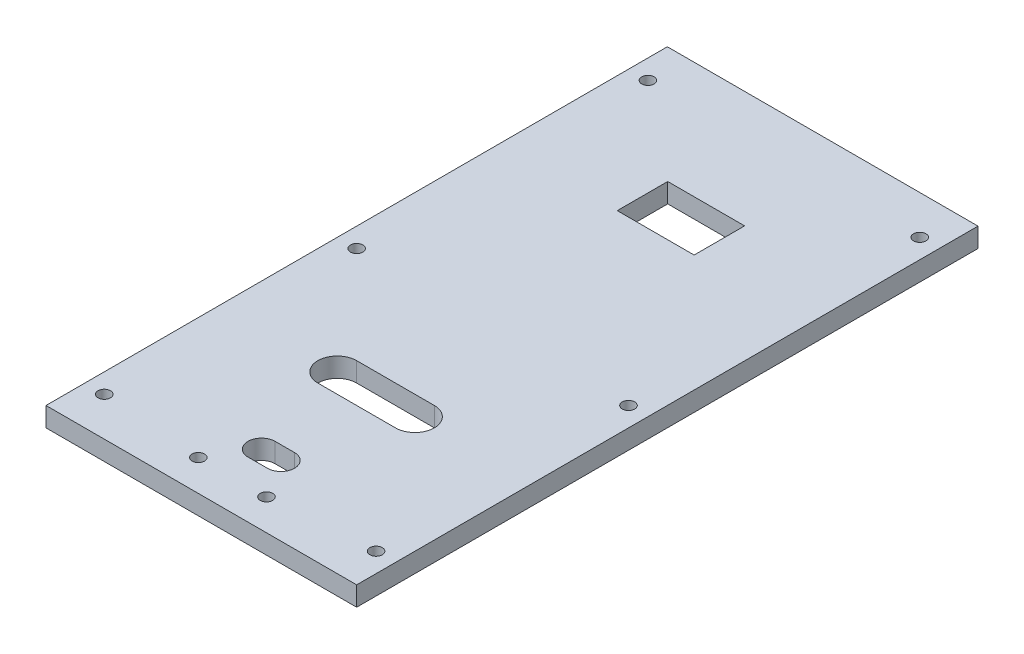
SolidWorks part; units mm, degrees
ref_plane "Plan de face" through (0, 0, 0) normal (0, 0, 1) x (1, 0, 0)
ref_plane "Plan de dessus" through (0, 0, 0) normal (0, 1, 0) x (1, 0, 0)
ref_plane "Plan de droite" through (0, 0, 0) normal (1, 0, 0) x (0, 0, -1)
sketch "Esquisse1" plane through (0, 0, 0) normal (0, 1, 0) x (1, 0, 0)
  line L1 (0, 0) -> (80, 0)
  line L2 (0, 0) -> (0, 160)
  line L3 (0, 160) -> (80, 160)
  line L4 (80, 0) -> (80, 160)
  dimension "D1" = 160
  dimension "D2" = 80
extrude "Boss.-Extru.1" add sketch "Esquisse1" along normal blind 5
sketch "Esquisse2" plane through (0, 0, 0) normal (0, 1, 0) x (1, 0, 0)
  line L0 (5, 160) -> (5, 0) construction
  line L1 (80, 160) -> (0, 160) construction
  line L2 (0, 0) -> (80, 0) construction
  line L3 (0, 160) -> (0, 0) construction
  line L4 (40, 160) -> (40, 0) construction
  circle A0 centre (5, 150) radius 1.6
  circle A1 centre (5, 75) radius 1.6
  circle A2 centre (5, 10) radius 1.6
  circle A3 centre (75, 10) radius 1.6
  circle A4 centre (75, 75) radius 1.6
  circle A5 centre (75, 150) radius 1.6
  dimension "D1" = 3.2
  dimension "D2" = 5
  dimension "D3" = 10
  dimension "D4" = 10
  dimension "D5" = 75
extrude "Enlèv. mat.-Extru.8" cut sketch "Esquisse2" along normal blind 10
sketch "Esquisse3" plane through (0, 0, 0) normal (0, 1, 0) x (1, 0, 0)
  line L0 (40, 160) -> (40, 0) construction
  line L1 (30.1, 130) -> (49.9, 130)
  line L2 (30.1, 130) -> (30.1, 117)
  line L3 (30.1, 117) -> (49.9, 117)
  line L4 (49.9, 130) -> (49.9, 117)
  line L5 (80, 160) -> (0, 160) construction
  line L6 (0, 0) -> (80, 0) construction
  point P10 (40, 130)
  dimension "D1" = 19.8
  dimension "D2" = 13
  dimension "D3" = 30
extrude "Enlèv. mat.-Extru.9" cut sketch "Esquisse3" along normal blind 10
sketch "Esquisse4" plane through (0, 5, 0) normal (0, 1, 0) x (1, 0, 0)
  line L0 (0, 8) -> (80, 8) construction
  line L1 (0, 160) -> (0, 0) construction
  line L2 (80, 0) -> (80, 160) construction
  line L3 (0, 0) -> (80, 0) construction
  line L4 (40, 160) -> (40, 0) construction
  line L5 (80, 160) -> (0, 160) construction
  circle A0 centre (31.225, 8) radius 1.6
  circle A1 centre (48.775, 8) radius 1.6
  dimension "D2" = 3.2
  dimension "D3" = 8.775
  dimension "D1" = 8
extrude "Enlèv. mat.-Extru.10" cut sketch "Esquisse4" against normal blind 10
sketch "Esquisse5" plane through (0, 5, 0) normal (0, 1, 0) x (1, 0, 0)
  line L0 (40, 160) -> (40, 0) construction
  line L1 (80, 160) -> (0, 160) construction
  line L2 (0, 0) -> (80, 0) construction
  line L3 (37.5, 18) -> (42.5, 18) construction
  line L4 (37.5, 21.5) -> (42.5, 21.5)
  line L5 (37.5, 14.5) -> (42.5, 14.5)
  arc A1 (37.5, 21.5) -> (37.5, 14.5) centre (37.5, 18) ccw
  arc A2 (42.5, 14.5) -> (42.5, 21.5) centre (42.5, 18) ccw
  point P8 (40, 18)
  dimension "D2" = 7
  dimension "D1" = 5
  dimension "D3" = 18
extrude "Enlèv. mat.-Extru.11" cut sketch "Esquisse5" against normal through all
sketch "Esquisse6" plane through (0, 5, 0) normal (0, 1, 0) x (1, 0, 0)
  line L0 (40, 0) -> (40, 160) construction
  line L1 (0, 0) -> (80, 0) construction
  line L2 (80, 160) -> (0, 160) construction
  line L3 (30, 45) -> (50, 45) construction
  line L4 (30, 50) -> (50, 50)
  line L5 (30, 40) -> (50, 40)
  arc A0 (30, 50) -> (30, 40) centre (30, 45) ccw
  arc A1 (50, 40) -> (50, 50) centre (50, 45) ccw
  point P8 (40, 45)
  dimension "D2" = 5
  dimension "D1" = 40
  dimension "D3" = 20
extrude "Enlèv. mat.-Extru.12" cut sketch "Esquisse6" against normal through all
